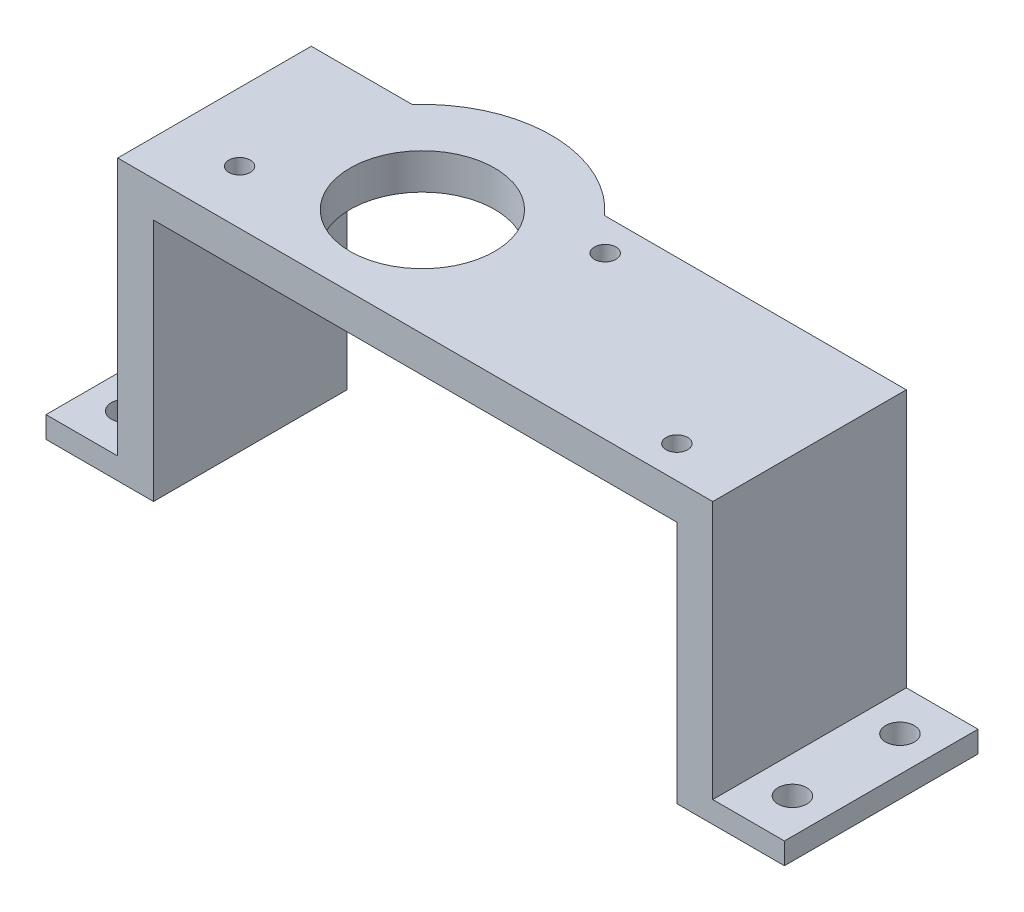
SolidWorks part; units mm, degrees
ref_plane "Front Plane" through (0, 0, 0) normal (0, 0, 1) x (1, 0, 0)
ref_plane "Top Plane" through (0, 0, 0) normal (0, 1, 0) x (1, 0, 0)
ref_plane "Right Plane" through (0, 0, 0) normal (1, 0, 0) x (0, 0, -1)
sketch "Sketch1" plane through (0, 0, 0) normal (0, 1, 0) x (1, 0, 0)
  line L0 (-26.897, -3.7209) -> (37.103, -3.7209)
  line L1 (37.103, -3.7209) -> (9.103, -3.7209)
  line L2 (9.103, -3.7209) -> (9.103, 14.2791)
  line L3 (-26.897, -3.7209) -> (-26.897, -0.7209)
  line L4 (-26.897, -0.7209) -> (9.103, 14.2791)
  line L5 (41.603, 18.7791) -> (-31.397, 18.7791)
  line L6 (41.603, 18.7791) -> (41.603, -8.2209)
  line L7 (41.603, -8.2209) -> (-31.397, -8.2209)
  line L8 (-31.397, 18.7791) -> (-31.397, -8.2209)
  circle A0 centre (-26.897, -0.7209) radius 1.5
  circle A1 centre (9.103, 14.2791) radius 1.5
  circle A2 centre (37.103, -3.7209) radius 1.5
  circle A3 centre (9.103, 14.2791) radius 4.5
  circle A4 centre (-26.897, -0.7209) radius 4.5
  circle A5 centre (37.103, -3.7209) radius 4.5
  circle A6 centre (-8.897, 6.7791) radius 10.0794
  circle A7 centre (-8.897, 6.7791) radius 18
  dimension "D5" = 3
  dimension "D6" = 3
  dimension "D7" = 3
  dimension "D8" = 9
  dimension "D9" = 9
  dimension "D10" = 9
  dimension "D1" = 64
  dimension "D2" = 28
  dimension "D3" = 18
  dimension "D4" = 3
  dimension "D11" = 4.5
  dimension "D12" = 4.5
  dimension "D13" = 4.5
  dimension "D14" = 4.5
extrude "Boss-Extrude1" add sketch "Sketch1" along normal blind 5
sketch "Sketch2" plane through (0, 5, 0) normal (0, 1, 0) x (1, 0, 0)
  line L1 (-31.397, 18.7791) -> (-36.397, 18.7791)
  line L2 (-31.397, 18.7791) -> (-31.397, -8.2209)
  line L3 (-31.397, -8.2209) -> (-36.397, -8.2209)
  line L4 (-36.397, 18.7791) -> (-36.397, -8.2209)
  line L5 (41.603, 18.7791) -> (46.603, 18.7791)
  line L6 (41.603, 18.7791) -> (41.603, -8.2209)
  line L7 (41.603, -8.2209) -> (46.603, -8.2209)
  line L8 (46.603, 18.7791) -> (46.603, -8.2209)
  line L9 (-34.9059, 18.7791) -> (-34.0123, 18.7791)
  line L10 (-34.9059, 18.7791) -> (-34.9059, 23.0122)
  line L11 (-34.9059, 23.0122) -> (-34.0123, 23.0122)
  line L12 (-34.0123, 18.7791) -> (-34.0123, 23.0122)
  line M7 (-31.397, 18.7791) -> (-31.397, -8.2209)
  line M11 (41.603, -8.2209) -> (41.603, 18.7791)
  dimension "D1" = 5
  dimension "D2" = 5
extrude "Boss-Extrude2" add sketch "Sketch2" against normal blind 39 contours L1 L4 L3 M7 | L8 L5 L7 M11
sketch "Sketch3" plane through (0, -34, 0) normal (0, -1, 0) x (1, 0, 0)
  line L0 (56.603, 8.2209) -> (56.603, -18.7791)
  line L1 (-36.397, 8.2209) -> (-46.397, 8.2209)
  line L2 (-36.397, 8.2209) -> (-36.397, -18.7791)
  line L3 (-36.397, -18.7791) -> (-46.397, -18.7791)
  line L4 (-46.397, 8.2209) -> (-46.397, -18.7791)
  line L5 (56.603, 8.2209) -> (46.603, 8.2209)
  line L6 (46.603, 8.2209) -> (46.603, -18.7791)
  line L7 (56.603, -18.7791) -> (46.603, -18.7791)
  circle A0 centre (-41.2846, 2.2209) radius 2
  circle A1 centre (-41.2846, -12.7791) radius 2
  circle A2 centre (51.7154, 2.2209) radius 2
  circle A3 centre (51.7154, -12.7791) radius 2
  dimension "D2" = 4
  dimension "D3" = 4
  dimension "D1" = 10
  dimension "D4" = 15
  dimension "D5" = 27
  dimension "D6" = 6
  dimension "D7" = 6
extrude "Boss-Extrude3" add sketch "Sketch3" against normal blind 3
